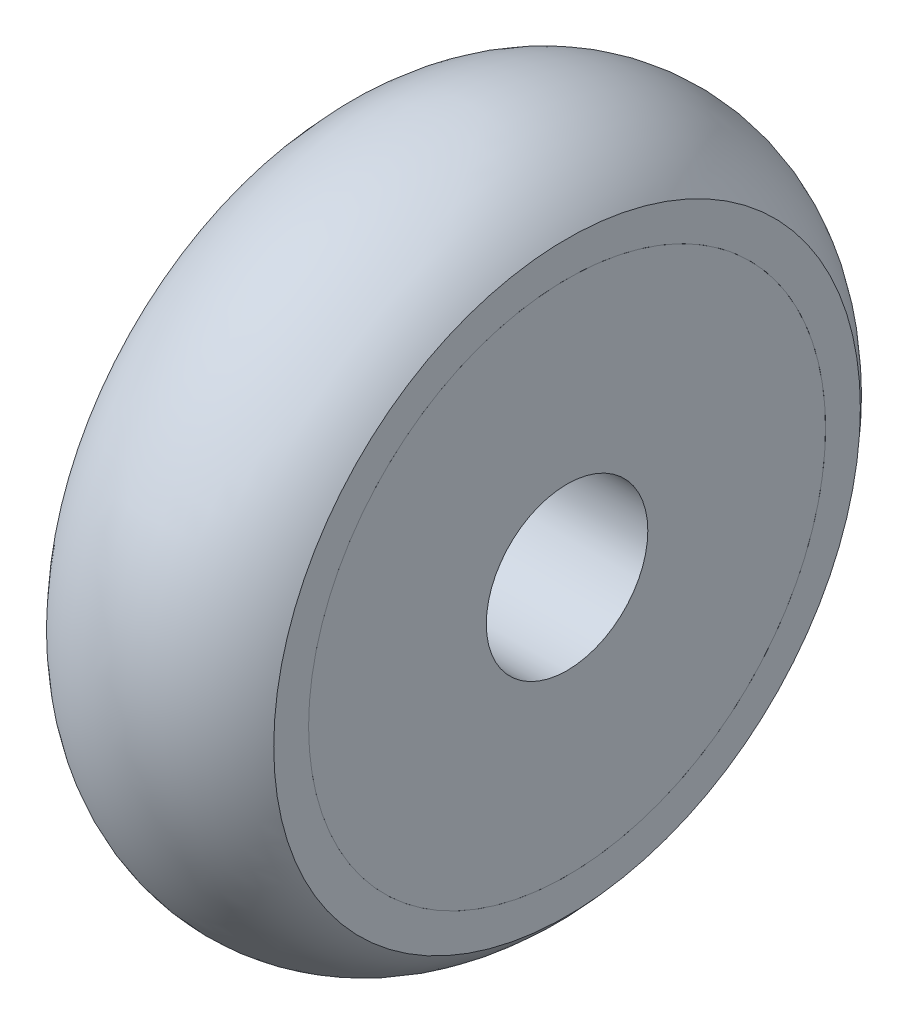
SolidWorks part; units mm, degrees
ref_plane "Спереди (Плоскость XY)" through (0, 0, 0) normal (0, 0, 1) x (1, 0, 0)
ref_plane "Сверху (Плоскость XZ)" through (0, 0, 0) normal (0, 1, 0) x (1, 0, 0)
ref_plane "Справа (Плоскость ZY)" through (0, 0, 0) normal (1, 0, 0) x (0, 0, -1)
sketch "Эскиз2" plane through (0, 0, 0) normal (0, 0, 1) x (1, 0, 0)
  line L0 (0, 20.1619) -> (0, -18.4181) construction
  line L1 (3.5, 8) -> (-3.5, 8)
  line L2 (-3.5, 8) -> (-3.5, 9.0784)
  line L3 (-4.9173, 0) -> (4.024, 0) construction
  line L4 (3.5, 8) -> (3.5, 9.0784)
  arc A2 (-3.5, 9.0784) -> (3.5, 9.0784) centre (0, 6.25) cw
  point P4 (0, 10.75)
  point P15 (0, 8)
  dimension "D3" = 21.5
  dimension "D1" = 4.5
  dimension "D2" = 16
  dimension "D4" = 7
revolve "Повернуть1" add sketch "Эскиз2" angle 360 about L3
sketch "Эскиз3" plane through (0, 0, 0) normal (1, 0, 0) x (0, 0, -1)
  circle A0 centre (0, 0) radius 2.5
  circle A1 centre (0, 0) radius 8
  dimension "D1" = 16
  dimension "D2" = 5
extrude "Бобышка-Вытянуть1" add sketch "Эскиз3" against normal up to surface (7 mm away) from surface at 3.5 separate body up to face at (-3.5, 0, 8) starting at face at (3.5, 0, 9.0784)
